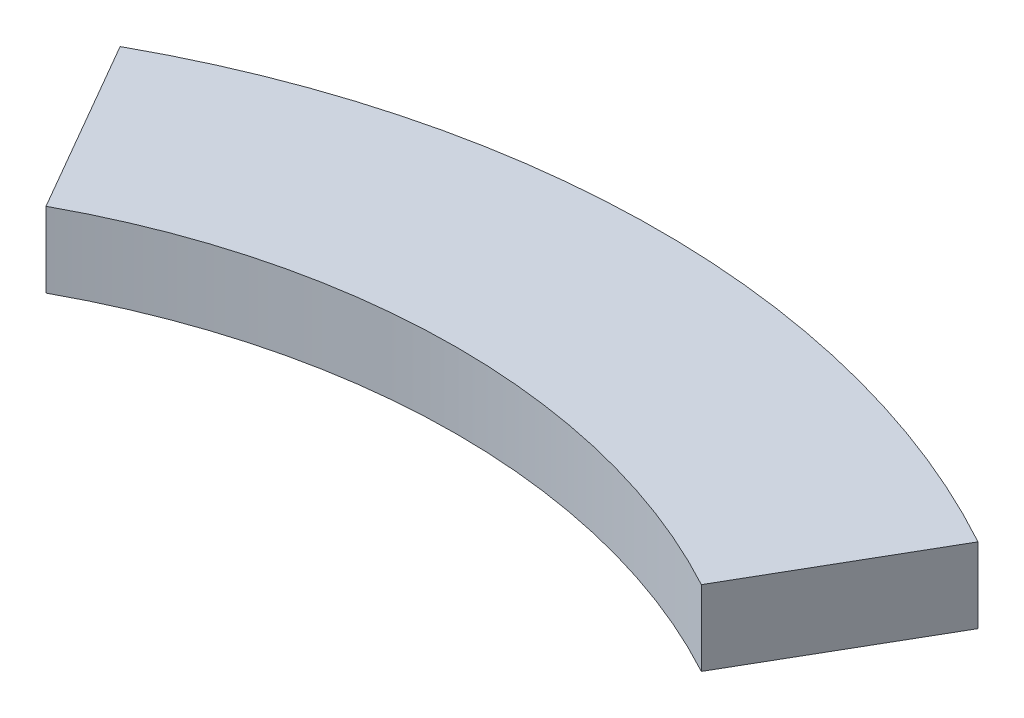
SolidWorks part; units mm, degrees
ref_plane "Front Plane" through (0, 0, 0) normal (0, 0, 1) x (1, 0, 0)
ref_plane "Top Plane" through (0, 0, 0) normal (0, 1, 0) x (1, 0, 0)
ref_plane "Right Plane" through (0, 0, 0) normal (1, 0, 0) x (0, 0, -1)
sketch "Sketch1" plane through (0, 0, 0) normal (0, 1, 0) x (1, 0, 0)
  line L0 (-14, 24.2487) -> (-19, 32.909) construction
  line L1 (14, 24.2487) -> (19, 32.909) construction
  line L2 (0, 0) -> (4, 0) construction
  line L3 (-17.9717, 32.6279) -> (-13.7293, 25.2798)
  line L4 (17.9717, 32.6279) -> (13.7293, 25.2798)
  line L5 (-16.5, 28.5788) -> (-15.8505, 28.9538) construction
  line L6 (15.8505, 28.9538) -> (16.5, 28.5788) construction
  circle A0 centre (0, 0) radius 28 construction
  circle A1 centre (0, 0) radius 38 construction
  arc A2 (-17.9717, 32.6279) -> (17.9717, 32.6279) centre (0, 0) cw
  arc A3 (-13.7293, 25.2798) -> (13.7293, 25.2798) centre (0, 0) cw
  point P19 (16.5, 28.5788)
  dimension "D1" = 28
  dimension "D2" = 38
  dimension "D4" = 0.75
  dimension "D6" = 60
  dimension "D3" = 60
  dimension "D5" = 0.75
extrude "Boss-Extrude1" add sketch "Sketch1" along normal blind 3.15
sketch "Sketch2" plane through (0, 0, 0) normal (0, -1, 0) x (1, 0, 0)
  line L0 (0, -37.25) -> (0, -28.7673) construction
  arc A0 (-17.9717, -32.6279) -> (17.9717, -32.6279) centre (0, 0) ccw construction
  arc A1 (-13.7293, -25.2798) -> (13.7293, -25.2798) centre (0, 0) ccw construction
  circle A2 centre (0, -33.0087) radius 1.625
  dimension "D1" = 3.25
extrude "Cut-Extrude1" cut sketch "Sketch2" against normal blind 2
